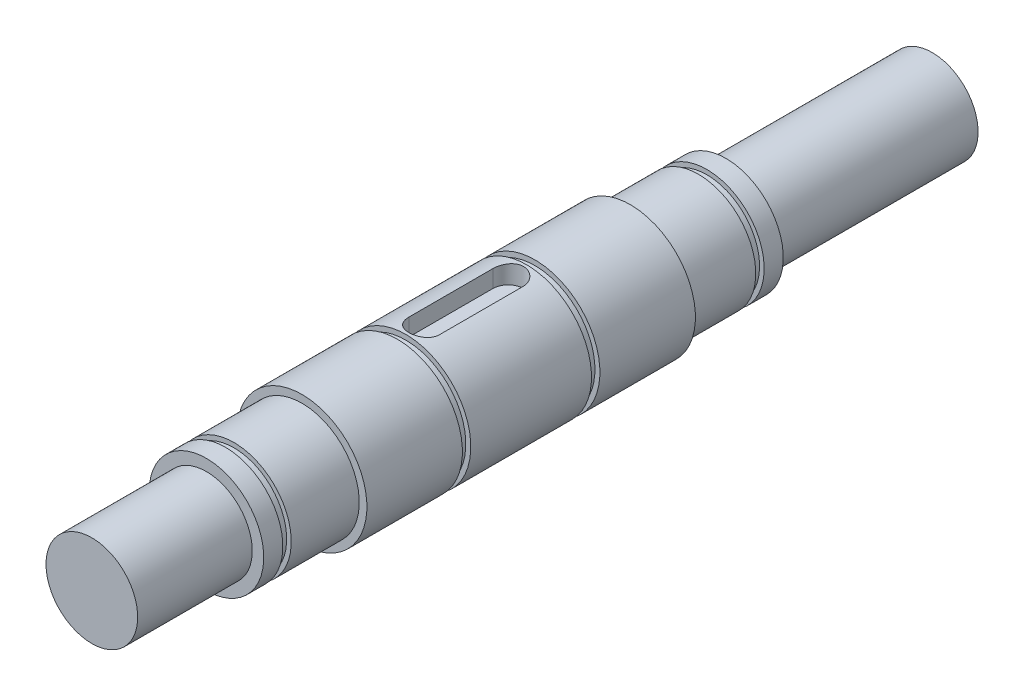
SolidWorks part; units mm, degrees
material "Plain Carbon Steel"
ref_plane "Front Plane" through (0, 0, 0) normal (0, 0, 1) x (1, 0, 0)
ref_plane "Top Plane" through (0, 0, 0) normal (0, 1, 0) x (1, 0, 0)
ref_plane "Right Plane" through (0, 0, 0) normal (1, 0, 0) x (0, 0, -1)
sketch "Sketch1" plane through (0, 0, 0) normal (0, 0, 1) x (1, 0, 0)
  circle A0 centre (0, 0) radius 8.5
  dimension "D1" = 17
extrude "Boss-Extrude1" add sketch "Sketch1" along normal mid plane 122
ref_axis "Axis1" through (0, 0, -67.1) along (0, 0, 1)
sketch "Sketch2" plane through (0, 0, 0) normal (1, 0, 0) x (0, 0, -1)
  line L0 (61, 8.5) -> (-61, 8.5) construction
  line L1 (21.5, 8.5) -> (61, 8.5)
  line L2 (21.5, 8.5) -> (21.5, 7.5)
  line L3 (21.5, 7.5) -> (61, 7.5)
  line L4 (61, 8.5) -> (61, 7.5)
  line L5 (61, -8.5) -> (61, 8.5) construction
  line L6 (67.1, 0) -> (-67.1, 0) construction
  dimension "D1" = 21.5
  dimension "D2" = 7.5
revolve "Cut-Revolve1" cut sketch "Sketch2" angle 360 about axis through (0, 0, -67.1) along (0, 0, 1)
mirror "Mirror1" about plane through (0, 0, 0) normal (0, 0, 1) of "Cut-Revolve1"
sketch "Sketch3" plane through (0, 0, 0) normal (1, 0, 0) x (0, 0, -1)
  line L0 (61, 7.5) -> (21.5, 7.5) construction
  line L1 (34, 7.5) -> (61, 7.5)
  line L2 (34, 7.5) -> (34, 6)
  line L3 (34, 6) -> (61, 6)
  line L4 (61, 7.5) -> (61, 6)
  line L5 (61, -7.5) -> (61, 7.5) construction
  line L6 (67.1, 0) -> (-67.1, 0) construction
  dimension "D1" = 27
  dimension "D2" = 6
revolve "Cut-Revolve2" cut sketch "Sketch3" angle 360 about axis through (0, 0, -67.1) along (0, 0, 1)
mirror "Mirror2" about plane through (0, 0, 0) normal (0, 0, 1) of "Cut-Revolve2"
sketch "Sketch4" plane through (0, 0, 0) normal (1, 0, 0) x (0, 0, -1)
  line L0 (34, 7.5) -> (21.5, 7.5) construction
  line L1 (30.4, 7.5) -> (31.5, 7.5)
  line L2 (30.4, 7.5) -> (30.4, 6.9)
  line L3 (30.4, 6.9) -> (31.5, 6.9)
  line L4 (31.5, 7.5) -> (31.5, 6.9)
  line L5 (21.5, -8.5) -> (21.5, 8.5) construction
  line L6 (67.1, 0) -> (-67.1, 0) construction
  dimension "D1" = 10
  dimension "D2" = 1.1
  dimension "D3" = 6.9
revolve "Cut-Revolve3" cut sketch "Sketch4" angle 360 about axis through (0, 0, -67.1) along (0, 0, 1)
mirror "Mirror3" about plane through (0, 0, 0) normal (0, 0, 1) of "Cut-Revolve3"
sketch "Sketch5" plane through (0, 0, 0) normal (1, 0, 0) x (0, 0, -1)
  line L0 (21.5, 8.5) -> (-21.5, 8.5) construction
  line L1 (7.9, 8.5) -> (9, 8.5)
  line L2 (7.9, 8.5) -> (7.9, 7.85)
  line L3 (7.9, 7.85) -> (9, 7.85)
  line L4 (9, 8.5) -> (9, 7.85)
  line L5 (67.1, 0) -> (-67.1, 0) construction
  dimension "D1" = 9
  dimension "D2" = 1.1
  dimension "D3" = 7.85
revolve "Cut-Revolve4" cut sketch "Sketch5" angle 360 about axis through (0, 0, -67.1) along (0, 0, 1)
mirror "Mirror4" about plane through (0, 0, 0) normal (0, 0, 1) of "Cut-Revolve4"
sketch "Sketch6" plane through (0, 0, 0) normal (1, 0, 0) x (0, 0, -1)
  line L0 (-61, -6) -> (-34, -6) construction
  line L1 (-61, 6) -> (-49, 6)
  line L2 (-61, 6) -> (-61, -6)
  line L3 (-61, -6) -> (-49, -6)
  line L4 (-49, 6) -> (-49, -6)
  dimension "D1" = 12
extrude "Cut-Extrude1" cut sketch "Sketch6" against normal through all both and the other way through all
ref_plane "Plane1" through (0, 8.5, 0) normal (0, 1, 0) x (1, 0, 0)
sketch "Sketch8" plane through (0, 8.5, 0) normal (0, 1, 0) x (1, 0, 0)
  line L0 (-2, -5.5) -> (-2, 5.5)
  line L1 (0, 67.1) -> (0, -67.1) construction
  line L2 (0, 0) -> (-11.0848, 0) construction
  line L3 (0, 0) -> (0, 7.4788) construction
  line L4 (2, -5.5) -> (2, 5.5)
  arc A0 (-2, 5.5) -> (2, 5.5) centre (0, 5.5) cw
  arc A1 (-2, -5.5) -> (2, -5.5) centre (0, -5.5) ccw
  point P10 (-2, 0)
  dimension "D1" = 11
  dimension "D2" = 4
extrude "Cut-Extrude2" cut sketch "Sketch8" against normal blind 2.5
